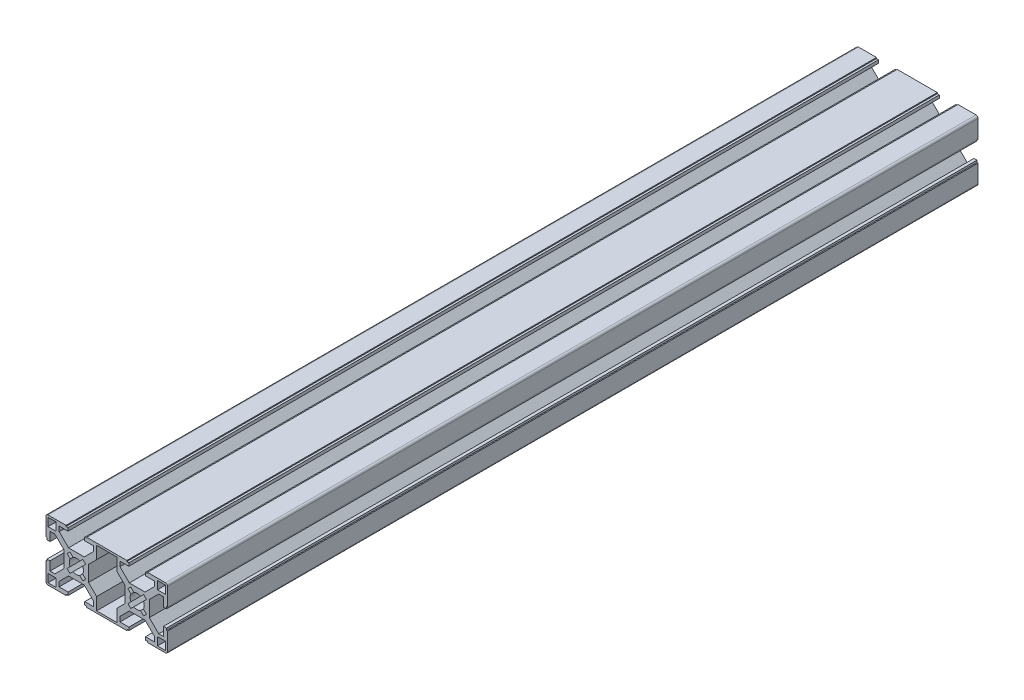
SolidWorks part; units mm, degrees
material "6063-T83"
ref_plane "Plano frontal" through (0, 0, 0) normal (0, 0, 1) x (1, 0, 0)
ref_plane "Plano superior" through (0, 0, 0) normal (0, 1, 0) x (1, 0, 0)
ref_plane "Plano direito" through (0, 0, 0) normal (1, 0, 0) x (0, 0, -1)
sketch "Esboço1" plane through (0, 0, 0) normal (0, 0, 1) x (1, 0, 0)
  line L5 (0, 0) -> (-17.7944, 17.7944) construction
  line L6 (0, 3.5) -> (0, 6)
  line L8 (0, 6) -> (-3.8787, 6)
  line L9 (-3.5, 0) -> (-6, 0)
  line L48 (-6, 0) -> (-6, 3.8787)
  line L49 (-3.8787, 6) -> (-8.5, 10.6213)
  line L50 (-6, 3.8787) -> (-10.6213, 8.5)
  line L51 (0, 0) -> (-12.921, 0) construction
  line L52 (-8.5, 13) -> (-4.1, 13)
  line L53 (-4.1, 13) -> (-4.1, 14.5)
  line L54 (-4.1, 14.5) -> (-5.1, 14.5)
  line L55 (-5.1, 14.5) -> (-5.1, 15)
  line L56 (-5.1, 15) -> (-15, 15)
  line L57 (-15, 5.1) -> (-15, 15)
  line L58 (-14.5, 5.1) -> (-15, 5.1)
  line L59 (-14.5, 4.1) -> (-14.5, 5.1)
  line L60 (-13, 4.1) -> (-14.5, 4.1)
  line L61 (-13, 8.5) -> (-13, 4.1)
  line L62 (-1.6646, 3.0788) -> (-3.182, 4.5962)
  line L63 (-3.0788, 1.6646) -> (-4.5962, 3.182)
  line L64 (-4.5962, 3.182) -> (-3.182, 4.5962)
  line L65 (-8.5, 13) -> (-8.5, 10.6213)
  line L66 (-10, 14) -> (-14, 14)
  line L67 (-10, 14) -> (-10, 10)
  line L68 (-10, 10) -> (-14, 10)
  line L69 (-14, 14) -> (-14, 10)
  line L70 (-10, 14) -> (-14, 10) construction
  line L71 (-10, 10) -> (-14, 14) construction
  line L72 (-13, 8.5) -> (-10.6213, 8.5)
  circle A1 centre (0, 0) radius 3.5
  point P25 (-12, 12)
  dimension "D5" = 10.9
  dimension "D9" = 5.5
  dimension "D10" = 2
  dimension "D11" = 4
  dimension "D12" = 4
  dimension "D13" = 1
  dimension "D1" = 7
  dimension "D2" = 6
  dimension "D3" = 3
  dimension "D4" = 9.9
  dimension "D6" = 0.5
  dimension "D7" = 1.5
  dimension "D8" = 15
  dimension "D14" = 6.5
extrude "Ressalto-extrusão1" add sketch "Esboço1" along normal blind 400 contours A1 L6 L8 L49 L65 L52 L53 L54 L55 L56 L57 L58 L59 L60 L61 L72 L50 L48 L9 L63 L64 L62 L69 L66 L67 L68
sketch "Esboço3" plane through (0, 0, 0) normal (1, 0, 0) x (0, 0, -1)
  line L0 (0, 0) -> (-1000, 0) construction
  dimension "D1" = 1000
pattern_circular "PadrãoCircular1" count 4 every 90 about axis through (0, 0, 0) along (0, 0, 1) of "Ressalto-extrusão1"
pattern_linear "Padrão linear1" count 2 spacing 30 along (1, 0, 0) of "Ressalto-extrusão1", "PadrãoCircular1"
sketch "Esboço4" plane through (0, 0, 0) normal (0, 0, -1) x (-1, 0, 0)
  line L0 (-20, 14) -> (-20, -14)
  line L1 (-20, -14) -> (-10, -14)
  line L2 (-10, -14) -> (-10, 14)
  line L3 (-10, 14) -> (-20, 14)
extrude "Corte-extrusão1" cut sketch "Esboço4" against normal through all
fillet "Filete1" radius 1 4 edges at (45, -15, 200) (45, 15, 200) (-15, 15, 200) (-15, -15, 200)
